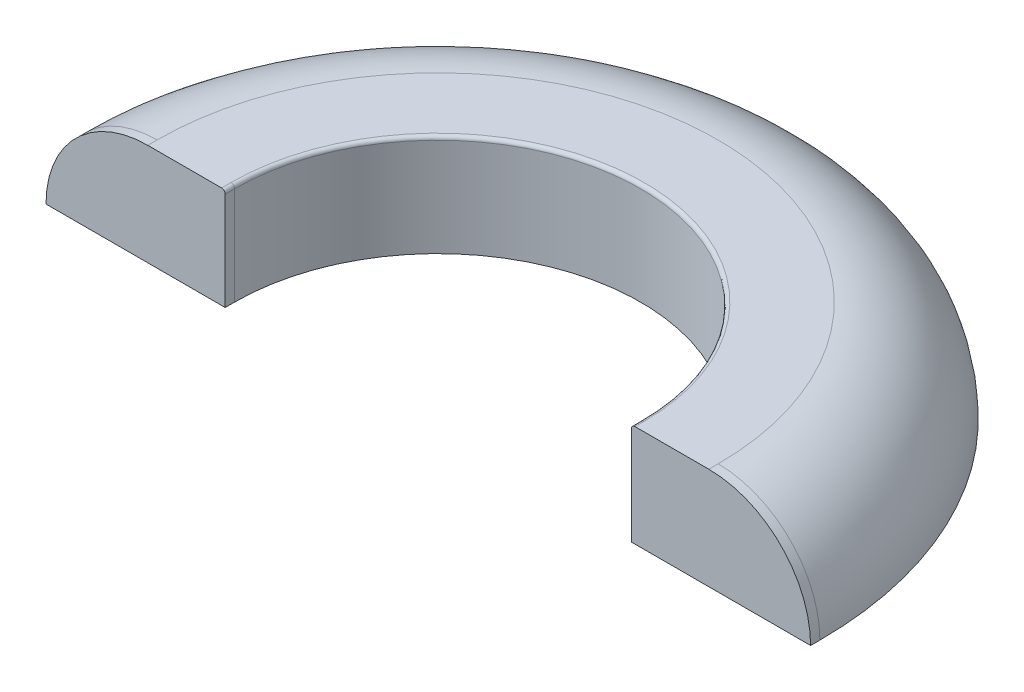
SolidWorks part; units mm, degrees
ref_plane "Front Plane" through (0, 0, 0) normal (0, 0, 1) x (1, 0, 0)
ref_plane "Top Plane" through (0, 0, 0) normal (0, 1, 0) x (1, 0, 0)
ref_plane "Right Plane" through (0, 0, 0) normal (1, 0, 0) x (0, 0, -1)
sketch "Sketch1" plane through (0, 0, 0) normal (0, 1, 0) x (1, 0, 0)
  line L0 (-566.6, 0) -> (-1066.6, 0)
  line L1 (566.6, 0) -> (1066.6, 0)
  arc A0 (-566.6, 0) -> (566.6, 0) centre (0, 0) cw
  arc A1 (-1066.6, 0) -> (1066.6, 0) centre (0, 0) cw
  dimension "D1" = 566.6
  dimension "D2" = 1066.6
extrude "Boss-Extrude1" add sketch "Sketch1" along normal blind 500
fillet "Fillet1" radius 10 4 edges at (0, 500, -1066.6) (0, 0, -1066.6) (0, 0, -566.6) (0, 500, -566.6)
sketch "Sketch2" plane through (0, 0, 0) normal (0, 0, 1) x (1, 0, 0)
  line L0 (-1056.6, 500) -> (-576.6, 500) construction
  line L1 (-1066.6, 490) -> (-1066.6, 10) construction
  line L4 (0, 0) -> (0, 618.5675) construction
  line L5 (-1066.6, 216) -> (-566.6, 216)
  line L6 (-566.6, 490) -> (-566.6, 10) construction
  line L7 (-566.6, 216) -> (-566.6, 0)
  line L8 (-576.6, 0) -> (576.6, 0) construction
  line L9 (-566.6, 0) -> (-1145.8611, 0)
  line L10 (-1145.8611, 0) -> (-1145.8611, 500)
  line L11 (-782.6, 500) -> (-1145.8611, 500)
  arc A0 (-782.6, 500) -> (-1066.6, 216) centre (-782.6, 216) ccw
  dimension "D1" = 568
revolve "Cut-Revolve1" cut sketch "Sketch2" angle 360 about L4
sketch "Sketch3" plane through (0, 0, 0) normal (0, 0, 1) x (1, 0, 0)
  line L0 (-782.6, 500) -> (-576.6, 500) construction
  line L1 (-566.6, 490) -> (-566.6, 216) construction
  line L2 (-566.6, 216) -> (-1066.6, 216) construction
  line L3 (-782.6, 500) -> (-576.6, 500)
  line L4 (-566.6, 490) -> (-566.6, 216)
  line L5 (-566.6, 216) -> (-1066.6, 216)
  line L6 (576.6, 500) -> (782.6, 500) construction
  line L7 (1066.6, 216) -> (566.6, 216) construction
  line L8 (566.6, 490) -> (566.6, 216) construction
  line L9 (576.6, 500) -> (782.6, 500)
  line L10 (1066.6, 216) -> (566.6, 216)
  line L11 (566.6, 490) -> (566.6, 216)
  arc A0 (-566.6, 490) -> (-576.6, 500) centre (-576.6, 490) ccw construction
  arc A1 (-782.6, 500) -> (-1066.6, 216) centre (-782.6, 216) ccw construction
  arc A2 (-566.6, 490) -> (-576.6, 500) centre (-576.6, 490) ccw
  arc A3 (-782.6, 500) -> (-1066.6, 216) centre (-782.6, 216) ccw
  arc A4 (576.6, 500) -> (566.6, 490) centre (576.6, 490) ccw construction
  arc A5 (1066.6, 216) -> (782.6, 500) centre (782.6, 216) ccw construction
  arc A6 (576.6, 500) -> (566.6, 490) centre (576.6, 490) ccw
  arc A7 (1066.6, 216) -> (782.6, 500) centre (782.6, 216) ccw
extrude "Boss-Extrude2" add sketch "Sketch3" along normal blind 26
